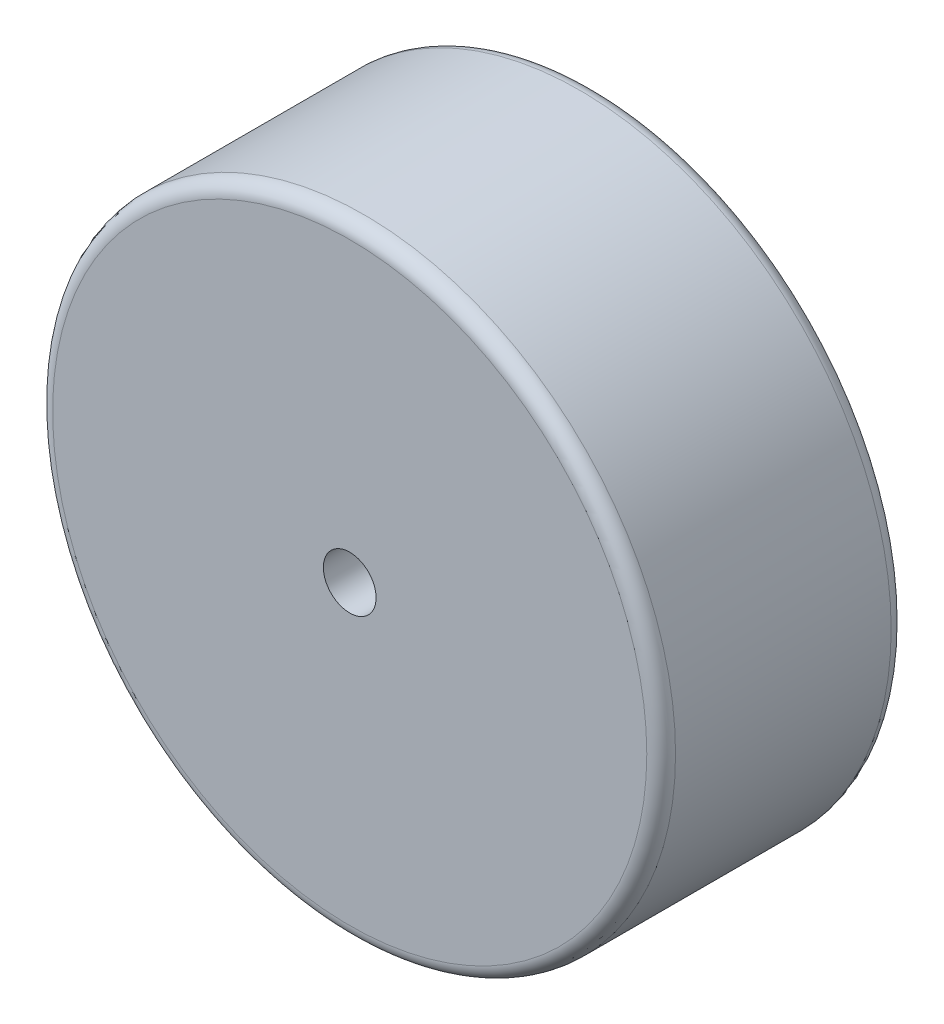
SolidWorks part; units mm, degrees
material "Q235-A"
ref_plane "前视基准面" through (0, 0, 0) normal (0, 0, 1) x (1, 0, 0)
ref_plane "上视基准面" through (0, 0, 0) normal (0, 1, 0) x (1, 0, 0)
ref_plane "右视基准面" through (0, 0, 0) normal (1, 0, 0) x (0, 0, -1)
sketch "草图1" plane through (0, 0, 0) normal (0, 0, 1) x (1, 0, 0)
  circle A0 centre (0, 0) radius 65
  dimension "D1" = 130
extrude "凸台-拉伸1" add sketch "草图1" along normal blind 51
sketch "草图2" plane through (0, 0, 51) normal (0, 0, 1) x (1, 0, 0)
  circle A0 centre (0, 0) radius 5.5
  dimension "D1" = 11
extrude "切除-拉伸1" cut sketch "草图2" against normal through all
fillet "圆角1" radius 3 2 edges at (65, 0, 51) (65, 0, 0)
